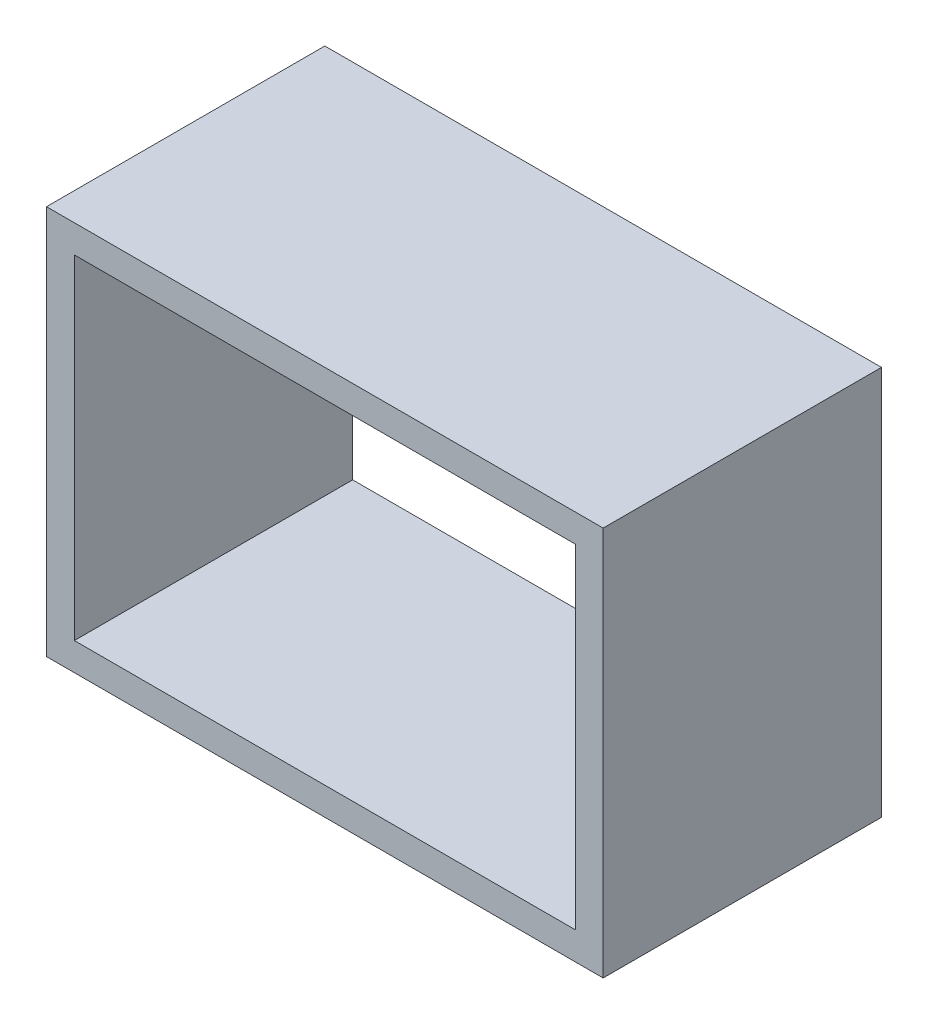
SolidWorks part; units mm, degrees
ref_plane "Front Plane" through (0, 0, 0) normal (0, 0, 1) x (1, 0, 0)
ref_plane "Top Plane" through (0, 0, 0) normal (0, 1, 0) x (1, 0, 0)
ref_plane "Right Plane" through (0, 0, 0) normal (1, 0, 0) x (0, 0, -1)
sketch "Sketch1" plane through (0, 0, 0) normal (0, 0, 1) x (1, 0, 0)
  line L1 (-90, 60) -> (90, 60)
  line L2 (-90, 60) -> (-90, -60)
  line L3 (-90, -60) -> (90, -60)
  line L4 (90, 60) -> (90, -60)
  line L5 (-90, 60) -> (90, -60) construction
  line L6 (-90, -60) -> (90, 60) construction
  point P0 (0, 0)
  dimension "D1" = 180
  dimension "D2" = 120
extrude "Extrude-Thin1" add sketch "Sketch1" along normal blind 100 thin thin type one direction wall 10
